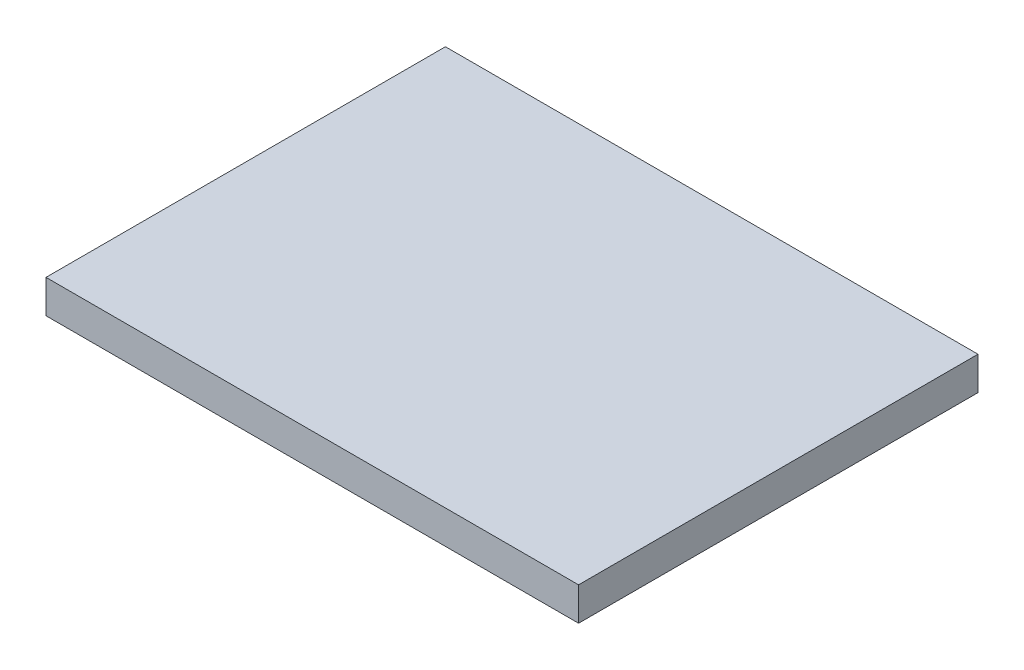
SolidWorks part; units mm, degrees
material "AISI 1015 Steel, Cold Drawn (SS)"
ref_plane "Front Plane" through (0, 0, 0) normal (0, 0, 1) x (1, 0, 0)
ref_plane "Top Plane" through (0, 0, 0) normal (0, 1, 0) x (1, 0, 0)
ref_plane "Right Plane" through (0, 0, 0) normal (1, 0, 0) x (0, 0, -1)
sketch "Sketch1" plane through (0, 0, 0) normal (0, 1, 0) x (1, 0, 0)
  line L1 (0, 0) -> (50.8, 0)
  line L2 (0, 0) -> (0, 38.1)
  line L3 (0, 38.1) -> (50.8, 38.1)
  line L4 (50.8, 0) -> (50.8, 38.1)
  dimension "D1" = 38.1
  dimension "D2" = 50.8
extrude "Boss-Extrude1" add sketch "Sketch1" along normal blind 3.175
